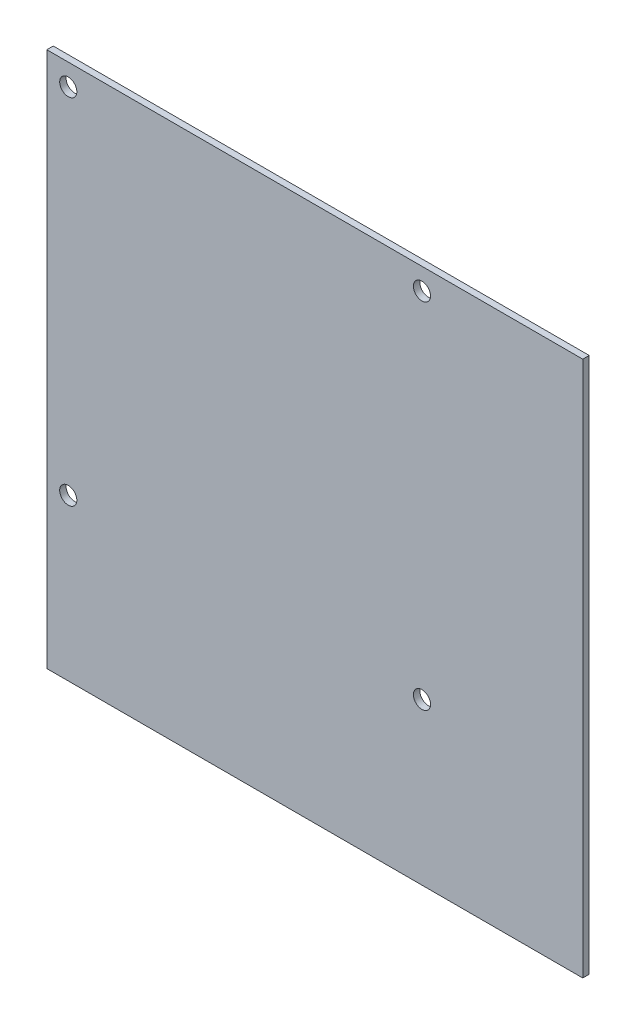
SolidWorks part; units mm, degrees
ref_plane "正面" through (0, 0, 0) normal (0, 0, 1) x (1, 0, 0)
ref_plane "平面" through (0, 0, 0) normal (0, 1, 0) x (1, 0, 0)
ref_plane "右側面" through (0, 0, 0) normal (1, 0, 0) x (0, 0, -1)
sketch "ｽｹｯﾁ1" plane through (0, 0, 0) normal (0, 0, 1) x (1, 0, 0)
  line L1 (-125, 125) -> (125, 125)
  line L2 (-125, 125) -> (-125, -125)
  line L3 (-125, -125) -> (125, -125)
  line L4 (125, 125) -> (125, -125)
  line L5 (-125, 125) -> (125, -125) construction
  line L6 (-125, -125) -> (125, 125) construction
  point P0 (0, 0)
  dimension "D1" = 250
  dimension "D2" = 250
extrude "ﾎﾞｽ - 押し出し1" add sketch "ｽｹｯﾁ1" along normal blind 3
sketch "ｽｹｯﾁ2" plane through (0, 0, 3) normal (0, 0, 1) x (1, 0, 0)
  line L0 (125, 125) -> (-125, 125) construction
  line L1 (-125, 125) -> (-125, -125) construction
  circle A0 centre (-115, 115) radius 4
  circle A1 centre (50, 115) radius 4
  circle A2 centre (-115, -50) radius 4
  circle A3 centre (50, -50) radius 4
  dimension "D1" = 8
  dimension "D2" = 10
  dimension "D3" = 10
  dimension "D4" = 8
  dimension "D6" = 165
  dimension "D7" = 8
  dimension "D8" = 10
  dimension "D9" = 165
  dimension "D10" = 8
  dimension "D11" = 165
  dimension "D12" = 165
  dimension "D5" = 10
extrude "ｶｯﾄ - 押し出し1" cut sketch "ｽｹｯﾁ2" against normal blind 3
